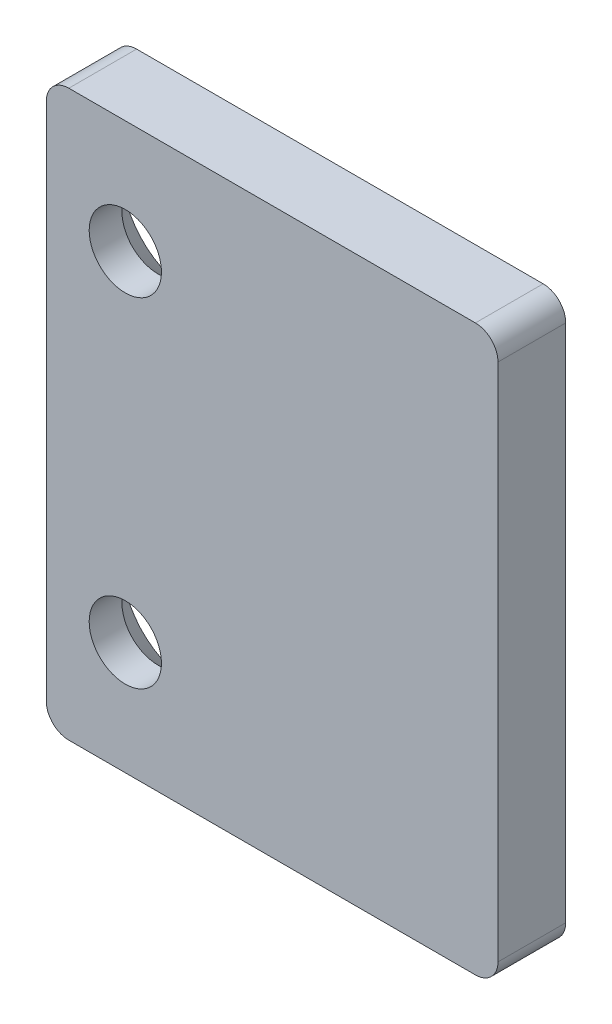
SolidWorks part; units mm, degrees
material "3.1325 (EN-AW 2017A)"
ref_plane "Front Plane" through (0, 0, 0) normal (0, 0, 1) x (1, 0, 0)
ref_plane "Top Plane" through (0, 0, 0) normal (0, 1, 0) x (1, 0, 0)
ref_plane "Right Plane" through (0, 0, 0) normal (1, 0, 0) x (0, 0, -1)
sketch "ｽｹｯﾁ1" plane through (0, 0, 0) normal (0, 0, 1) x (1, 0, 0)
  line L0 (3.5, 25) -> (3.5, 0) construction
  line L1 (0, 0) -> (20, 0)
  line L2 (0, 0) -> (0, 25)
  line L3 (0, 25) -> (20, 25)
  line L4 (20, 0) -> (20, 25)
  line L5 (0, 0) -> (20, 25) construction
  line L6 (0, 25) -> (20, 0) construction
  circle A0 centre (3.5, 5) radius 1.6
  circle A1 centre (3.5, 20) radius 1.6
  point P4 (10, 12.5)
  dimension "D3" = 3.2
  dimension "D6" = 15
  dimension "D1" = 20
  dimension "D2" = 3.5
  dimension "D5" = 5
  dimension "D7" = 5
extrude "ﾎﾞｽ - 押し出し1" add sketch "ｽｹｯﾁ1" along normal blind 3
fillet "ﾌｨﾚｯﾄ1" radius 1 4 edges at (0, 25, 1.5) (20, 25, 1.5) (0, 0, 1.5) (20, 0, 1.5)
hole_wizard "M3 丸皿ねじ用皿穴1" positions "ｽｹｯﾁ2" profile "ｽｹｯﾁ3" countersink size "M3" standard "JIS" end condition through all
sketch "ｽｹｯﾁ2" plane through (0, 0, 0) normal (0, 0, -1) x (-1, 0, 0)
  point P0 (-3.5, 20)
  point P3 (-3.5, 5)
sketch "ｽｹｯﾁ3" plane through (3.5, 20, 0) normal (1, 0, 0) x (0, 1, 0)
  line L0 (0, 0) -> (0, 3)
  line L1 (0, 3) -> (1.55, 3)
  line L2 (1.55, 3) -> (1.55, 1.6)
  line L3 (1.55, 1.6) -> (3.15, 0)
  line L5 (3.15, 0) -> (0, 0)
  line L6 (-1.55, 1.6) -> (-3.15, 0) construction
  line L11 (0, -6.35) -> (0, 107.95) construction
  dimension "通し穴の直径" = 3.1
  dimension "通し穴の深さ" = 3
  dimension "表面の皿穴の直径" = 6.3
  dimension "表面の皿穴の角度" = 90
